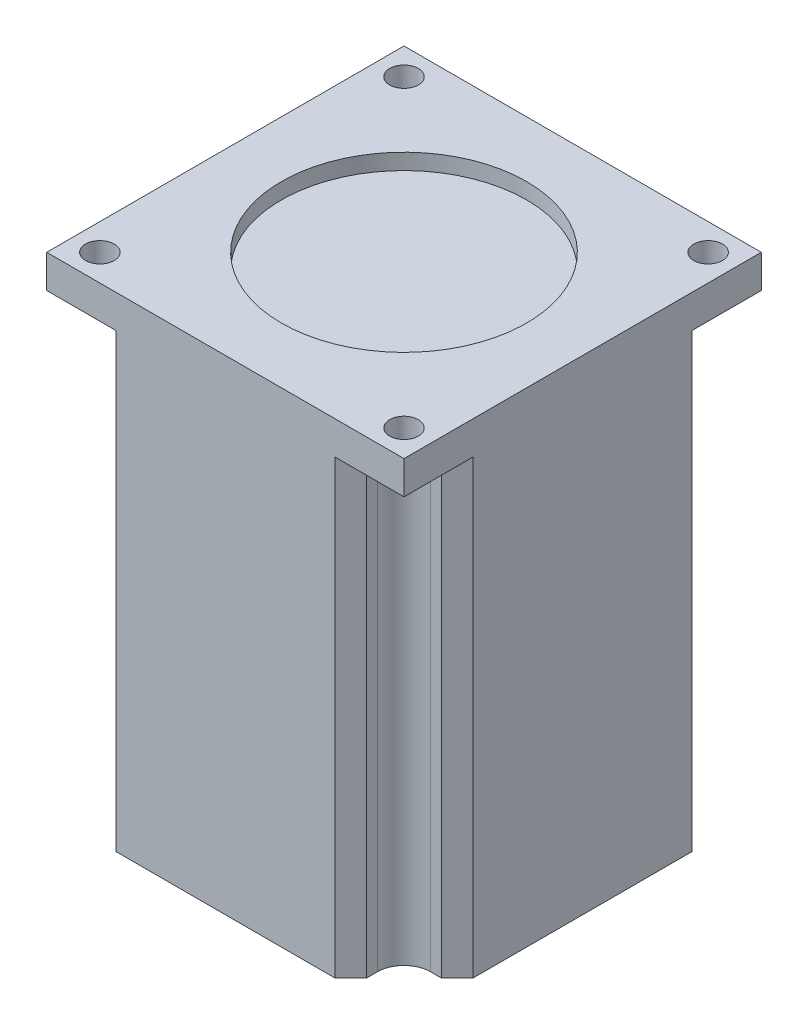
SolidWorks part; units mm, degrees
ref_plane "Alzado" through (0, 0, 0) normal (0, 0, 1) x (1, 0, 0)
ref_plane "Planta" through (0, 0, 0) normal (0, 1, 0) x (1, 0, 0)
ref_plane "Vista lateral" through (0, 0, 0) normal (1, 0, 0) x (0, 0, -1)
sketch "Croquis1" plane through (0, 0, 0) normal (0, 1, 0) x (1, 0, 0)
  line L1 (28.05, 28.05) -> (-28.05, 28.05)
  line L2 (28.05, 28.05) -> (28.05, -28.05)
  line L3 (28.05, -28.05) -> (-28.05, -28.05)
  line L4 (-28.05, 28.05) -> (-28.05, -28.05)
  line L5 (28.05, 28.05) -> (-28.05, -28.05) construction
  line L6 (28.05, -28.05) -> (-28.05, 28.05) construction
  point P0 (0, 0)
  dimension "D1" = 56.1
extrude "Saliente-Extruir1" add sketch "Croquis1" along normal blind 76.05
ref_plane "Plano1" through (0, 70.85, 0) normal (0, 1, 0) x (1, 0, 0)
sketch "Croquis2" plane through (0, 70.85, 0) normal (0, 1, 0) x (1, 0, 0)
  line L0 (-28.05, 19.7) -> (-23.875, 19.7)
  line L3 (-28.05, 28.05) -> (-28.05, -28.05) construction
  line L4 (-19.7, 23.875) -> (-19.7, 28.05)
  line L6 (28.05, 28.05) -> (-28.05, 28.05) construction
  line L7 (-28.05, 19.7) -> (-28.05, 28.05)
  line L8 (-28.05, 28.05) -> (-19.7, 28.05)
  arc A0 (-23.875, 19.7) -> (-19.7, 23.875) centre (-23.875, 23.875) ccw
  point P11 (-28.05, 23.875)
  dimension "D1" = 8.35
extrude "Cortar-Extruir1" cut sketch "Croquis2" against normal through all
mirror "Simetría3" about plane through (0, 0, 0) normal (1, 0, 0) of "Cortar-Extruir1" second plane through (0, 0, 0) second plane normal (0, 0, 1)
chamfer "Chaflán1" distance 2.5 angle 45 8 edges at (-28.05, 35.425, -19.7) (-19.7, 35.425, -28.05) (-28.05, 35.425, 19.7) (-19.7, 35.425, 28.05) (28.05, 35.425, -19.7) (19.7, 35.425, -28.05) (28.05, 35.425, 19.7) (19.7, 35.425, 28.05)
sketch "Croquis3" plane through (0, 70.85, 0) normal (0, -1, 0) x (1, 0, 0)
  circle A1 centre (23.875, -23.875) radius 2.25
  arc A2 (23.875, -19.7) -> (19.7, -23.875) centre (23.875, -23.875) ccw construction
  dimension "D1" = 4.5
extrude "Cortar-Extruir2" cut sketch "Croquis3" against normal through all
mirror "Simetría4" about plane through (0, 0, 0) normal (1, 0, 0) of "Cortar-Extruir2" second plane through (0, 0, 0) second plane normal (0, 0, 1)
sketch "Croquis4" plane through (0, 76.05, 0) normal (0, 1, 0) x (1, 0, 0)
  circle A0 centre (0, 0) radius 19.25
  dimension "D1" = 38.5
extrude "Cortar-Extruir3" cut sketch "Croquis4" against normal blind 2.5
